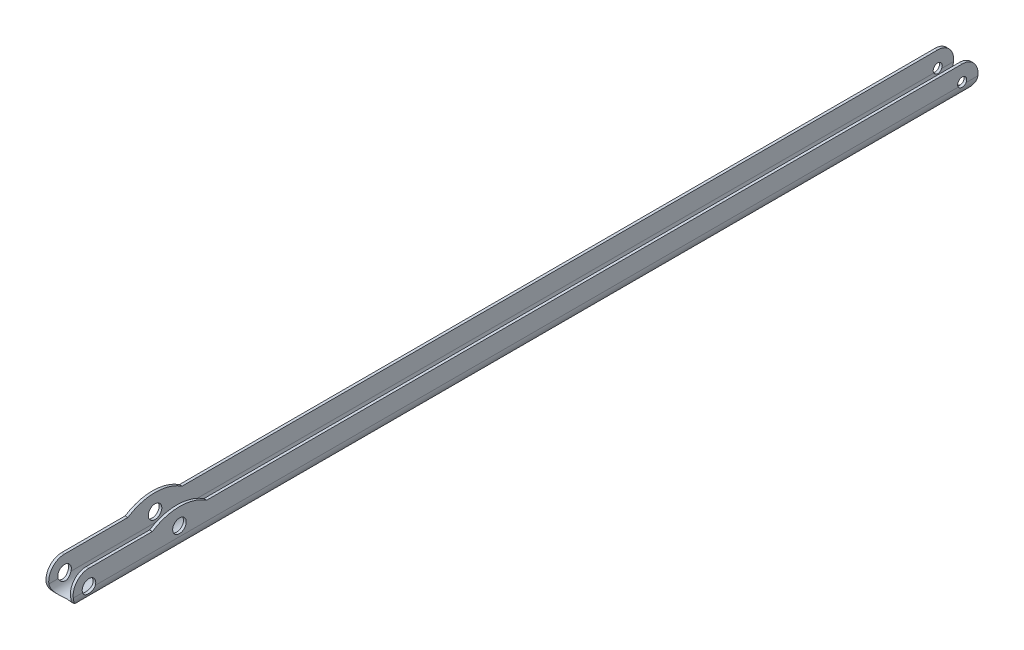
SolidWorks part; units mm, degrees
ref_plane "Piano frontale" through (0, 0, 0) normal (0, 0, 1) x (1, 0, 0)
ref_plane "Piano superiore" through (0, 0, 0) normal (0, 1, 0) x (1, 0, 0)
ref_plane "Piano destro" through (0, 0, 0) normal (1, 0, 0) x (0, 0, -1)
sketch "Schizzo1" plane through (0, 0, 0) normal (0, 0, 1) x (1, 0, 0)
  line L0 (0, -55) -> (0, 55) construction
  line L1 (-1.5, -18) -> (-1.2, -18)
  line L2 (-1.5, -18) -> (-1.5, -20)
  line L3 (55, 0) -> (-55, 0) construction
  line L4 (1.5, -18) -> (1.5, -20)
  line L5 (-1.2, -18) -> (-1.2, -20)
  line L6 (1.2, -18) -> (1.2, -20)
  line L7 (1.2, -18) -> (1.5, -18)
  line L8 (-1.2, -18.3) -> (-1.2, -20) construction
  line L9 (1.2, -18.3) -> (1.2, -20) construction
  line L10 (-1.2, -18.3) -> (1.2, -18.3) construction
  line L12 (-1.5, -18) -> (1.5, -18) construction
  arc A0 (-1.5, -20) -> (1.5, -20) centre (0, -20) ccw
  arc A1 (-1.2, -20) -> (1.2, -20) centre (0, -20) ccw
  dimension "D1" = 3
  dimension "D2" = 20
  dimension "D3" = 2
  dimension "D4" = 0.3
extrude "Estrusione-Estrusione1" add sketch "Schizzo1" along normal blind 100
sketch "Schizzo2" plane through (1.5, 0, 0) normal (1, 0, 0) x (0, 0, -1)
  line L0 (-100, -18) -> (0, -18) construction
  line L2 (-100, -20) -> (-100, -18) construction
  line L3 (-98.25, -18) -> (-98.25, -16.5636)
  line L4 (-98.25, -16.5636) -> (-100.9883, -16.5636)
  line L5 (-100.9883, -16.5636) -> (-100.9883, -22.3053)
  line L6 (-100.9883, -22.3053) -> (-98.25, -22.3053)
  line L7 (-98.25, -22.3053) -> (-98.25, -21.5)
  line L8 (0, 1.65) -> (0, -1.65) construction
  line L9 (-1.75, -18) -> (-1.75, -17.0142)
  line L10 (-1.75, -17.0142) -> (0.7839, -17.0142)
  line L11 (0.7839, -17.0142) -> (0.7839, -22.1081)
  line L12 (0.7839, -22.1081) -> (-1.75, -22.1081)
  line L13 (-1.75, -22.1081) -> (-1.75, -21.5)
  circle A0 centre (-98.25, -19.75) radius 0.75
  arc A1 (-98.25, -18) -> (-98.25, -21.5) centre (-98.25, -19.75) ccw
  circle A2 centre (-88.25, -18.95) radius 0.75
  circle A3 centre (-1.75, -19.75) radius 0.5
  arc A4 (-1.75, -21.5) -> (-1.75, -18) centre (-1.75, -19.75) ccw
  dimension "D2" = 1.5
  dimension "D6" = 1.5
  dimension "D10" = 1
  dimension "D1" = 1.75
  dimension "D3" = 2.7383
  dimension "D4" = 1.4364
  dimension "D5" = 5.7417
  dimension "D7" = 10
  dimension "D8" = 0.8
  dimension "D9" = 1.75
  dimension "D11" = 2.5339
  dimension "D12" = 0.9858
  dimension "D13" = 5.0939
extrude "Taglio-Estrusione5" cut sketch "Schizzo2" against normal blind 100
sketch "Schizzo3" plane through (1.5, 0, 0) normal (1, 0, 0) x (0, 0, -1)
  line L0 (-98.25, -18) -> (-1.75, -18) construction
  line L2 (-91.25, -18) -> (-85.25, -18)
  arc A0 (-91.25, -18) -> (-85.25, -18) centre (-88.25, -22.6098) cw
  circle A1 centre (-88.25, -18.95) radius 0.75 construction
  dimension "D2" = 3
  dimension "D3" = 5.5
  dimension "D1" = 3
extrude "Estrusione-Estrusione2" add sketch "Schizzo3" along direction (1, 0, 0) on the side against the normal up to surface (0.3 mm away)
sketch "Schizzo4" plane through (-1.5, 0, 0) normal (-1, 0, 0) x (0, 0, 1)
  line L0 (98.25, -18) -> (1.75, -18) construction
  line L1 (91.25, -18) -> (85.25, -18)
  arc A0 (91.25, -18) -> (85.25, -18) centre (88.25, -22.6098) ccw construction
  arc A1 (91.25, -18) -> (85.25, -18) centre (88.25, -22.6098) ccw
extrude "Estrusione-Estrusione3" add sketch "Schizzo4" against normal up to vertex (0.3 mm away) up to point (-1.2, -18, 98.25)
